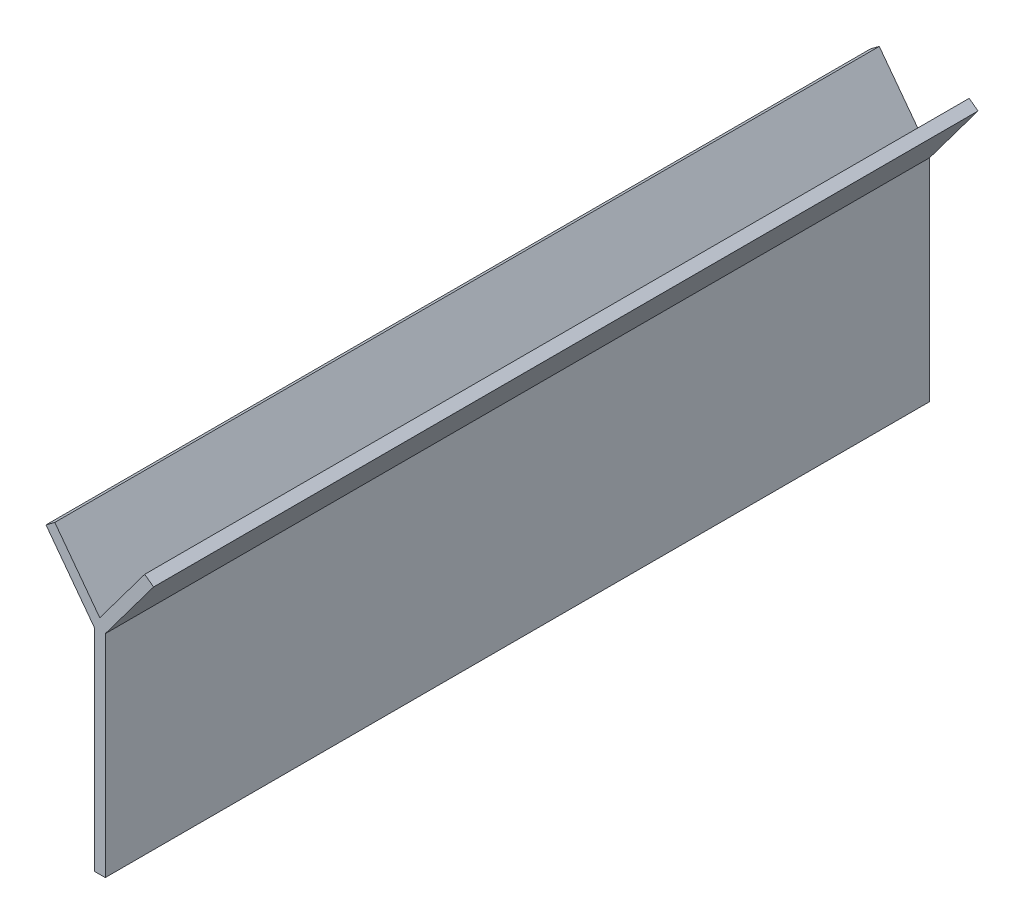
SolidWorks part; units mm, degrees
ref_plane "前视基准面" through (0, 0, 0) normal (0, 0, 1) x (1, 0, 0)
ref_plane "上视基准面" through (0, 0, 0) normal (0, 1, 0) x (1, 0, 0)
ref_plane "右视基准面" through (0, 0, 0) normal (1, 0, 0) x (0, 0, -1)
sketch "草图1" plane through (0, 0, 0) normal (0, 0, 1) x (1, 0, 0)
  line L3 (0, 3.34) -> (-16.3623, 25.2245)
  line L4 (2, -0.665) -> (19.5658, 22.8293)
  line L5 (-2, -0.665) -> (-2, -77.5401)
  line L6 (-2, -0.665) -> (-19.5658, 22.8293)
  line L7 (0, 3.34) -> (16.3623, 25.2245)
  line L8 (2, -0.665) -> (2, -77.5401)
  line L9 (16.3623, 25.2245) -> (19.5658, 22.8293)
  line L10 (-16.3623, 25.2245) -> (-19.5658, 22.8293)
  line L11 (-2, -77.5401) -> (2, -77.5401)
  dimension "D5" = 4
  dimension "D6" = 4
  dimension "D7" = 4
extrude "凸台-拉伸1" add sketch "草图1" along normal blind 400
sketch "草图2" plane through (0, 0, 0) normal (0, 0, -1) x (-1, 0, 0)
  circle A0 centre (0, -10.3245) radius 93.1574
extrude "切除-拉伸1" cut sketch "草图2" against normal blind 100
